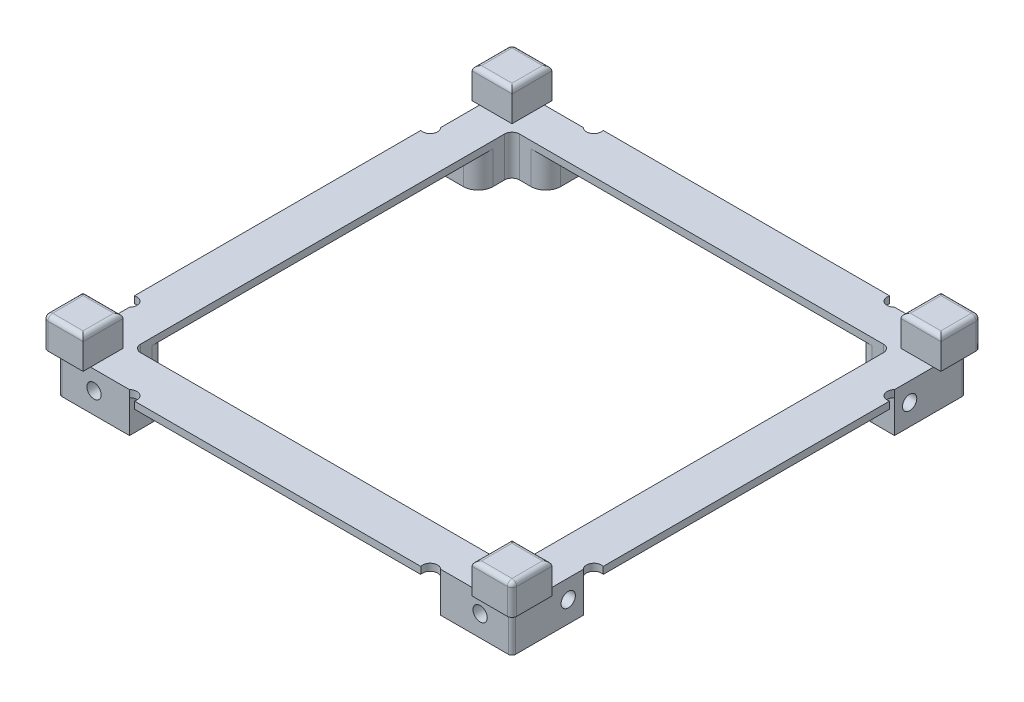
SolidWorks part; units mm, degrees
material "6061-T6 (SS)"
ref_plane "Front Plane" through (0, 0, 0) normal (0, 0, 1) x (1, 0, 0)
ref_plane "Top Plane" through (0, 0, 0) normal (0, 1, 0) x (1, 0, 0)
ref_plane "Right Plane" through (0, 0, 0) normal (1, 0, 0) x (0, 0, -1)
sketch "Sketch1" plane through (0, 0, 0) normal (0, 1, 0) x (1, 0, 0)
  line L1 (0, 0) -> (100, 0)
  line L2 (0, 0) -> (0, 100)
  line L3 (0, 100) -> (100, 100)
  line L4 (100, 0) -> (100, 100)
  dimension "D1" = 100
  dimension "D2" = 100
extrude "Boss-Extrude1" add sketch "Sketch1" along normal blind 8.5
sketch "Sketch2" plane through (0, 8.5, 0) normal (0, 1, 0) x (1, 0, 0)
  line L0 (0, 100) -> (19.05, 100)
  line L1 (100, 100) -> (0, 100) construction
  line L2 (0, 100) -> (0, 80.95)
  line L3 (0, 100) -> (0, 0) construction
  line L4 (1.5875, 98.4125) -> (1.5875, 83.1951)
  line L5 (1.5875, 98.4125) -> (16.8049, 98.4125)
  line L8 (1.5875, 80.95) -> (-2.2881, 84.8256) construction
  line L9 (19.05, 98.4125) -> (15.2408, 102.2217) construction
  line L10 (0, 80.95) -> (0, 80.5547)
  line L11 (1.5875, 98.4125) -> (1.5875, 80.95) construction
  line L12 (19.05, 100) -> (19.4453, 100)
  line L13 (1.5875, 98.4125) -> (19.05, 98.4125) construction
  line L14 (50, 100) -> (50, 0) construction
  line L15 (0, 0) -> (100, 0) construction
  line L16 (50, 0) -> (100, 50) construction
  line L17 (100, 0) -> (100, 100) construction
  line L18 (100, 50) -> (0, 50) construction
  line L19 (80.95, 98.4125) -> (84.7592, 102.2217) construction
  line L20 (98.4125, 80.95) -> (102.2881, 84.8256) construction
  line L21 (80.95, 100) -> (80.5547, 100)
  line L22 (100, 80.95) -> (100, 80.5547)
  line L23 (98.4125, 98.4125) -> (83.1951, 98.4125)
  line L24 (98.4125, 98.4125) -> (98.4125, 83.1951)
  line L25 (100, 100) -> (100, 80.95)
  line L26 (100, 100) -> (80.95, 100)
  line L27 (98.4125, 19.05) -> (102.2881, 15.1744) construction
  line L28 (80.95, 1.5875) -> (84.7592, -2.2217) construction
  line L29 (100, 0) -> (80.95, 0)
  line L30 (100, 0) -> (100, 19.05)
  line L31 (98.4125, 1.5875) -> (98.4125, 16.8049)
  line L32 (98.4125, 1.5875) -> (83.1951, 1.5875)
  line L33 (100, 19.05) -> (100, 19.4453)
  line L34 (80.95, 0) -> (80.5547, 0)
  line L35 (19.05, 1.5875) -> (15.2408, -2.2217) construction
  line L36 (1.5875, 19.05) -> (-2.2881, 15.1744) construction
  line L37 (19.05, 0) -> (19.4453, 0)
  line L38 (0, 19.05) -> (0, 19.4453)
  line L39 (1.5875, 1.5875) -> (16.8049, 1.5875)
  line L40 (1.5875, 1.5875) -> (1.5875, 16.8049)
  line L41 (0, 0) -> (0, 19.05)
  line L42 (0, 0) -> (19.05, 0)
  arc A1 (0, 83.5904) -> (-0.6576, 83.1951) centre (0.465, 82.0725) ccw
  arc A2 (16.8049, 98.4125) -> (19.4453, 100) centre (17.9275, 99.535) ccw
  arc A3 (0, 80.5547) -> (1.5875, 83.1951) centre (0.465, 82.0725) ccw
  arc A4 (100, 80.5547) -> (98.4125, 83.1951) centre (99.535, 82.0725) cw
  arc A5 (83.1951, 98.4125) -> (80.5547, 100) centre (82.0725, 99.535) cw
  arc A6 (100, 83.5904) -> (100.6576, 83.1951) centre (99.535, 82.0725) cw
  arc A7 (100, 16.4096) -> (100.6576, 16.8049) centre (99.535, 17.9275) ccw
  arc A8 (83.1951, 1.5875) -> (80.5547, 0) centre (82.0725, 0.465) ccw
  arc A9 (100, 19.4453) -> (98.4125, 16.8049) centre (99.535, 17.9275) ccw
  arc A10 (0, 19.4453) -> (1.5875, 16.8049) centre (0.465, 17.9275) cw
  arc A11 (16.8049, 1.5875) -> (19.4453, 0) centre (17.9275, 0.465) cw
  arc A12 (0, 16.4096) -> (-0.6576, 16.8049) centre (0.465, 17.9275) cw
  dimension "D4" = 45
  dimension "D5" = 1.5875
  dimension "D7" = 1.5875
  dimension "D1" = 19.05
  dimension "D2" = 19.05
  dimension "D6" = 45
  dimension "D3" = 1.5875
extrude "Cut-Extrude1" cut sketch "Sketch2" against normal through all
sketch "Sketch3" plane through (0, 8.5, 0) normal (0, 1, 0) x (1, 0, 0)
  line L0 (0, 50) -> (100, 50) construction
  line L5 (0, 0) -> (8.5, 0)
  line L6 (0, 0) -> (0, 8.5)
  line L7 (0, 8.5) -> (8.5, 8.5)
  line L8 (8.5, 0) -> (8.5, 8.5)
  line L9 (0, 80.5547) -> (0, 19.4453) construction
  line L10 (100, 19.4453) -> (100, 80.5547) construction
  line L11 (100, 50) -> (50, 100) construction
  line L12 (80.5547, 100) -> (19.4453, 100) construction
  line L13 (50, 100) -> (50, 0) construction
  line L14 (19.4453, 0) -> (80.5547, 0) construction
  line L15 (100, 8.5) -> (91.5, 8.5)
  line L16 (91.5, 0) -> (91.5, 8.5)
  line L17 (100, 0) -> (91.5, 0)
  line L18 (100, 0) -> (100, 8.5)
  line L19 (100, 100) -> (100, 91.5)
  line L20 (100, 100) -> (91.5, 100)
  line L21 (91.5, 100) -> (91.5, 91.5)
  line L22 (100, 91.5) -> (91.5, 91.5)
  line L23 (0, 91.5) -> (8.5, 91.5)
  line L24 (8.5, 100) -> (8.5, 91.5)
  line L25 (0, 100) -> (8.5, 100)
  line L26 (0, 100) -> (0, 91.5)
  dimension "D1" = 8.5
  dimension "D2" = 8.5
extrude "Boss-Extrude2" add sketch "Sketch3" along normal blind 6.5
sketch "Sketch10" plane through (0, 0, 0) normal (0, -1, 0) x (1, 0, 0)
  line L0 (100, -50) -> (0, -50) construction
  line L1 (100, -19.4453) -> (100, -80.5547) construction
  line L3 (0, -80.5547) -> (0, -19.4453) construction
  line L5 (50, 0) -> (50, -100) construction
  line L7 (19.4453, 0) -> (80.5547, 0) construction
  line L9 (80.5547, -100) -> (19.4453, -100) construction
  line L14 (90.005, -50) -> (90.005, -92.8625) construction
  line L15 (95.085, -2.0575) -> (4.915, -2.0575) construction
  line L16 (95.085, -2.0575) -> (95.085, -97.9425) construction
  line L17 (95.085, -97.9425) -> (4.915, -97.9425) construction
  line L18 (4.915, -2.0575) -> (4.915, -97.9425) construction
  line L19 (95.085, -2.0575) -> (4.915, -97.9425) construction
  line L20 (95.085, -97.9425) -> (4.915, -2.0575) construction
  line L21 (86.195, -50) -> (86.195, -7.1375) construction
  line L22 (12.535, -50) -> (12.535, -7.1375) construction
  line L23 (9.995, -50) -> (9.995, -92.8625) construction
  point P21 (50, -50)
  point P35 (12.535, -7.1375)
  point P36 (9.995, -92.8625)
  point P37 (90.005, -92.8625)
  point P38 (86.195, -7.1375)
  dimension "D1" = 95.885
  dimension "D2" = 90.17
  dimension "D3" = 5.08
  dimension "D4" = 8.89
  dimension "D5" = 5.08
  dimension "D6" = 5.08
  dimension "D7" = 7.62
  dimension "D8" = 5.08
  dimension "D9" = 5.08
  dimension "D10" = 5.08
hole_wizard "Tap Drill for #4 Helicoil5" positions "Sketch11" profile "Sketch12" hole size "#4-40" standard "ANSI Inch"
sketch "Sketch11" plane through (0, 0, 0) normal (0, -1, 0) x (-1, 0, 0)
  point P14 (-86.195, 7.1375)
  point P17 (-90.005, 92.8625)
  point P20 (-12.535, 7.1375)
  point P23 (-9.995, 92.8625)
sketch "Sketch12" plane through (86.195, 0, -7.1375) normal (1, 0, 0) x (0, 0, -1)
  line L0 (0, 0) -> (0, 6.6057)
  line L1 (0, 6.6057) -> (1.524, 5.69)
  line L2 (1.524, 5.69) -> (1.524, 0)
  line L5 (1.524, 0) -> (0, 0)
  line L10 (0, 6.6057) -> (-1.524, 5.69) construction
  line L11 (0, -6.35) -> (0, 107.95) construction
  dimension "Hole Dia." = 3.048
  dimension "Hole Depth" = 5.69
  dimension "Drill Angle" = 118
sketch "Sketch13" plane through (0, 15, 0) normal (0, 1, 0) x (1, 0, 0)
  line L0 (0, 50) -> (100, 50) construction
  line L1 (0, 0) -> (100, 0) construction
  line L2 (0, 0) -> (0, 100) construction
  line L3 (0, 100) -> (100, 100) construction
  line L4 (100, 0) -> (100, 100) construction
  line L5 (100, 50) -> (50, 100) construction
  line L6 (50, 100) -> (50, 0) construction
  line L7 (100, 0) -> (100, 4.25) construction
  line L8 (100, 4.25) -> (95.75, 4.25) construction
  point P11 (95.75, 95.75)
  point P13 (95.75, 4.25)
  point P14 (4.25, 95.75)
  point P15 (4.25, 4.25)
  dimension "D1" = 4.25
  dimension "D2" = 4.25
sketch "Sketch16" plane through (1.5875, 0, 0) normal (-1, 0, 0) x (0, 0, 1)
  line L0 (-98.4125, 4.5) -> (-83.1951, 4.5) construction
  line L1 (-98.4125, 0) -> (-98.4125, 8.5) construction
  line L4 (-91.5, 8.5) -> (-83.1951, 8.5) construction
  point P6 (-86.4125, 4.5)
  dimension "D1" = 12
  dimension "D2" = 4
hole_wizard "Tap Drill for #4 Helicoil5" positions "Sketch17" profile "Sketch18" hole size "#4-40" standard "ANSI Inch"
sketch "Sketch17" plane through (1.5875, 0, 0) normal (-1, 0, 0) x (0, 0, 1)
  point P0 (-86.4125, 4.5)
sketch "Sketch18" plane through (1.5875, 4.5, -86.4125) normal (0, 1, 0) x (0, 0, 1)
  line L0 (0, 0) -> (0, 6.6057)
  line L1 (0, 6.6057) -> (1.524, 5.69)
  line L2 (1.524, 5.69) -> (1.524, 0)
  line L5 (1.524, 0) -> (0, 0)
  line L10 (0, 6.6057) -> (-1.524, 5.69) construction
  line L11 (0, -6.35) -> (0, 107.95) construction
  dimension "Hole Dia." = 3.048
  dimension "Hole Depth" = 5.69
  dimension "Drill Angle" = 118
ref_plane "Plane6" through (50, 0, 0) normal (-1, 0, 0) x (0, 0, 1)
ref_plane "Plane7" through (0, 0, -50) normal (0, 0, -1) x (-1, 0, 0)
mirror "Mirror1" about plane through (0, 0, -50) normal (0, 0, -1) of "Tap Drill for #4 Helicoil5"
mirror "Mirror2" about plane through (50, 0, 0) normal (-1, 0, 0) of "Mirror1", "Tap Drill for #4 Helicoil5"
sketch "Sketch19" plane through (0, 0, -98.4125) normal (0, 0, -1) x (-1, 0, 0)
  line L0 (-1.5875, 4.5) -> (-16.8049, 4.5) construction
  line L2 (-1.5875, 0) -> (-1.5875, 8.5) construction
  line L3 (-8.5, 8.5) -> (-16.8049, 8.5) construction
  point P5 (-13.5875, 4.5)
  dimension "D1" = 12
  dimension "D2" = 4
hole_wizard "Tap Drill for #4 Helicoil5" positions "Sketch20" profile "Sketch21" hole size "#4-40" standard "ANSI Inch"
sketch "Sketch20" plane through (0, 0, -98.4125) normal (0, 0, -1) x (-1, 0, 0)
  point P0 (-13.5875, 4.5)
sketch "Sketch21" plane through (13.5875, 4.5, -98.4125) normal (1, 0, 0) x (0, 1, 0)
  line L0 (0, 0) -> (0, 6.6057)
  line L1 (0, 6.6057) -> (1.524, 5.69)
  line L2 (1.524, 5.69) -> (1.524, 0)
  line L5 (1.524, 0) -> (0, 0)
  line L10 (0, 6.6057) -> (-1.524, 5.69) construction
  line L11 (0, -6.35) -> (0, 107.95) construction
  dimension "Hole Dia." = 3.048
  dimension "Hole Depth" = 5.69
  dimension "Drill Angle" = 118
mirror "Mirror3" about plane through (50, 0, 0) normal (-1, 0, 0) of "Tap Drill for #4 Helicoil5"
sketch "Sketch33" plane through (0, 0, -1.5875) normal (0, 0, 1) x (1, 0, 0)
  line L2 (91.5, 8.5) -> (83.1951, 8.5) construction
  line L3 (98.4125, 0) -> (98.4125, 8.5) construction
  point P5 (91.6125, 4.5)
  dimension "D3" = 4
  dimension "D4" = 6.8
hole_wizard "Tap Drill for #4 Helicoil5" positions "Sketch34" profile "Sketch35" hole size "#4-40" standard "ANSI Inch"
sketch "Sketch34" plane through (0, 0, -1.5875) normal (0, 0, 1) x (1, 0, 0)
  point P6 (91.6125, 4.5)
sketch "Sketch35" plane through (91.6125, 4.5, -1.5875) normal (1, 0, 0) x (0, -1, 0)
  line L0 (0, 0) -> (0, 6.6057)
  line L1 (0, 6.6057) -> (1.524, 5.69)
  line L2 (1.524, 5.69) -> (1.524, 0)
  line L5 (1.524, 0) -> (0, 0)
  line L10 (0, 6.6057) -> (-1.524, 5.69) construction
  line L11 (0, -6.35) -> (0, 107.95) construction
  dimension "Hole Dia." = 3.048
  dimension "Hole Depth" = 5.69
  dimension "Drill Angle" = 118
sketch "Sketch22" plane through (0, 0, 0) normal (0, -1, 0) x (1, 0, 0)
  line L0 (50, 0) -> (50, -100) construction
  line L5 (83.1951, -9.5875) -> (88.825, -9.5875)
  line L6 (90.4125, -11.175) -> (90.4125, -16.8049)
  line L7 (50, -100) -> (0, -50) construction
  line L8 (0, -50) -> (100, -50) construction
  line L9 (1.5875, -16.8049) -> (9.5875, -16.8049)
  line L10 (16.8049, -1.5875) -> (16.8049, -9.5875)
  line L11 (9.5875, -11.175) -> (9.5875, -16.8049)
  line L12 (16.8049, -9.5875) -> (11.175, -9.5875)
  line L13 (83.1951, -1.5875) -> (83.1951, -9.5875)
  line L14 (98.4125, -16.8049) -> (90.4125, -16.8049)
  line L15 (98.4125, -83.1951) -> (90.4125, -83.1951)
  line L16 (83.1951, -98.4125) -> (83.1951, -90.4125)
  line L17 (16.8049, -90.4125) -> (11.175, -90.4125)
  line L18 (9.5875, -88.825) -> (9.5875, -83.1951)
  line L19 (16.8049, -98.4125) -> (16.8049, -90.4125)
  line L20 (1.5875, -83.1951) -> (9.5875, -83.1951)
  line L21 (90.4125, -88.825) -> (90.4125, -83.1951)
  line L22 (83.1951, -90.4125) -> (88.825, -90.4125)
  line L23 (1.5875, -83.1951) -> (0, -83.1951)
  line L24 (0, -83.1951) -> (0, -16.8049)
  line L25 (0, -16.8049) -> (1.5875, -16.8049)
  line L26 (16.8049, -1.5875) -> (16.8049, 0)
  line L27 (16.8049, 0) -> (83.1951, 0)
  line L28 (0, 0) -> (100, 0) construction
  line L29 (83.1951, 0) -> (83.1951, -1.5875)
  line L30 (98.4125, -83.1951) -> (100, -83.1951)
  line L31 (100, -16.8049) -> (98.4125, -16.8049)
  line L32 (100, -83.1951) -> (100, -16.8049)
  line L33 (16.8049, -98.4125) -> (16.8049, -100)
  line L34 (83.1951, -100) -> (83.1951, -98.4125)
  line L35 (16.8049, -100) -> (83.1951, -100)
  line L36 (80.5547, -100) -> (19.4453, -100) construction
  arc A4 (9.5875, -11.175) -> (11.175, -9.5875) centre (11.175, -11.175) cw
  arc A5 (90.4125, -11.175) -> (88.825, -9.5875) centre (88.825, -11.175) ccw
  arc A6 (90.4125, -88.825) -> (88.825, -90.4125) centre (88.825, -88.825) cw
  arc A7 (9.5875, -88.825) -> (11.175, -90.4125) centre (11.175, -88.825) ccw
  point P0 (50, -50)
  point P19 (90.4125, -9.5875)
  point P30 (9.5875, -9.5875)
  point P44 (9.5875, -90.4125)
  point P45 (90.4125, -90.4125)
  dimension "D4" = 1.5875
  dimension "D2" = 8
  dimension "D3" = 8
extrude "Cut-Extrude2" cut sketch "Sketch22" against normal blind 7
sketch "Sketch23" plane through (0, 7, 0) normal (0, -1, 0) x (1, 0, 0)
  line L0 (0, -50) -> (100, -50) construction
  line L1 (0, -19.4453) -> (0, -80.5547) construction
  line L2 (100, -80.5547) -> (100, -19.4453) construction
  line L4 (11.175, -90.4125) -> (88.825, -90.4125)
  line L5 (9.5875, -88.825) -> (9.5875, -11.175)
  line L6 (11.175, -9.5875) -> (88.825, -9.5875)
  line L7 (90.4125, -88.825) -> (90.4125, -11.175)
  line L8 (9.5875, -90.4125) -> (90.4125, -9.5875) construction
  line L9 (9.5875, -9.5875) -> (90.4125, -90.4125) construction
  arc A0 (90.4125, -88.825) -> (88.825, -90.4125) centre (88.825, -88.825) cw
  arc A1 (88.825, -9.5875) -> (90.4125, -11.175) centre (88.825, -11.175) cw
  arc A2 (11.175, -9.5875) -> (9.5875, -11.175) centre (11.175, -11.175) ccw
  arc A3 (9.5875, -88.825) -> (11.175, -90.4125) centre (11.175, -88.825) ccw
  arc A4 (9.5875, -88.825) -> (11.175, -90.4125) centre (11.175, -88.825) ccw construction
  point P6 (50, -50)
  dimension "D3" = 1.5875
extrude "Cut-Extrude3" cut sketch "Sketch23" against normal through all
fillet "Fillet1" radius 1 20 edges at (95.75, 15, 0) (100, 15, -4.25) (91.5, 15, -4.25) (95.75, 15, -8.5) (4.25, 15, 0) (8.5, 15, -4.25) (0, 15, -4.25) (4.25, 15, -8.5) (4.25, 15, -91.5) (8.5, 15, -95.75) (0, 15, -95.75) (4.25, 15, -100) (100, 15, -95.75) (95.75, 15, -91.5) (91.5, 15, -95.75) (95.75, 15, -100) (100, 11.75, -100) (0, 11.75, -100) (0, 11.75, 0) (100, 11.75, 0)
fillet "Fillet2" radius 3.175 8 edges at (9.5875, 3.5, -16.8049) (16.8049, 3.5, -9.5875) (9.5875, 3.5, -83.1951) (16.8049, 3.5, -90.4125) (83.1951, 3.5, -90.4125) (90.4125, 3.5, -83.1951) (83.1951, 3.5, -9.5875) (90.4125, 3.5, -16.8049)
fillet "Fillet3" radius 0.79 4 edges at (1.5875, 4.25, -1.5875) (98.4125, 4.25, -1.5875) (98.4125, 4.25, -98.4125) (1.5875, 4.25, -98.4125)
sketch "Sketch36" plane through (0, 0, -1.5875) normal (0, 0, 1) x (1, 0, 0)
  line L2 (8.5, 8.5) -> (16.8049, 8.5) construction
  line L3 (1.5875, 0) -> (1.5875, 8.5) construction
  point P5 (9.2475, 4.5)
  dimension "D3" = 4
  dimension "D4" = 7.66
hole_wizard "Tap Drill for #4 Helicoil5" positions "Sketch37" profile "Sketch38" hole size "#4-40" standard "ANSI Inch"
sketch "Sketch37" plane through (0, 0, -1.5875) normal (0, 0, 1) x (1, 0, 0)
  point P4 (9.2475, 4.5)
sketch "Sketch38" plane through (9.2475, 4.5, -1.5875) normal (1, 0, 0) x (0, -1, 0)
  line L0 (0, 0) -> (0, 6.6057)
  line L1 (0, 6.6057) -> (1.524, 5.69)
  line L2 (1.524, 5.69) -> (1.524, 0)
  line L5 (1.524, 0) -> (0, 0)
  line L10 (0, 6.6057) -> (-1.524, 5.69) construction
  line L11 (0, -6.35) -> (0, 107.95) construction
  dimension "Hole Dia." = 3.048
  dimension "Hole Depth" = 5.69
  dimension "Drill Angle" = 118
sketch "Sketch24" [suppressed] plane through (0, 15, 0) normal (0, 1, 0) x (1, 0, 0)
  line L0 (4.25, 99) -> (4.25, 92.5) construction
  line L3 (7.5, 99) -> (1, 99) construction
  line L6 (1, 92.5) -> (7.5, 92.5) construction
  line L7 (95.75, 7.5) -> (95.75, 1) construction
  line L8 (99, 7.5) -> (92.5, 7.5) construction
  line L9 (92.5, 1) -> (99, 1) construction
  point P14 (95.75, 4.25)
  point P15 (4.25, 95.75)
hole_wizard "Tap Drill for #8-32 Tap1" positions "Sketch25" profile "Sketch26" hole size "#8-32" standard "ANSI Inch"
sketch "Sketch25" plane through (0, 15, 0) normal (0, 1, 0) x (1, 0, 0)
  point P7 (4.25, 95.75)
  point P10 (95.75, 4.25)
sketch "Sketch26" plane through (4.25, 15, -95.75) normal (1, 0, 0) x (0, 0, 1)
  line L0 (0, 0) -> (0, 12.1376)
  line L1 (0, 12.1376) -> (1.7272, 11.0998)
  line L2 (1.7272, 11.0998) -> (1.7272, 0)
  line L5 (1.7272, 0) -> (0, 0)
  line L10 (0, 12.1376) -> (-1.7272, 11.0998) construction
  line L11 (0, -6.35) -> (0, 107.95) construction
  dimension "Hole Dia." = 3.4544
  dimension "Hole Depth" = 11.0998
  dimension "Drill Angle" = 118
sketch "Sketch27" [suppressed] plane through (0, 15, 0) normal (0, 1, 0) x (1, 0, 0)
  line L6 (95.75, 99) -> (95.75, 92.5) construction
  line L7 (99, 99) -> (92.5, 99) construction
  line L8 (92.5, 92.5) -> (99, 92.5) construction
  line L9 (4.25, 7.5) -> (4.25, 1) construction
  line L10 (7.5, 7.5) -> (1, 7.5) construction
  line L11 (1, 1) -> (7.5, 1) construction
  circle A2 centre (95.75, 95.75) radius 2.8575
  circle A3 centre (4.25, 4.25) radius 2.8575
  dimension "D1" = 5.715
  dimension "D3" = 5.715
extrude "Cut-Extrude4" [suppressed] cut sketch "Sketch27" against normal blind 2.032
sketch "Sketch28" [suppressed] plane through (0, 12.968, 0) normal (0, 1, 0) x (1, 0, 0)
  circle A2 centre (95.75, 95.75) radius 2.286
  circle A3 centre (4.25, 4.25) radius 2.286
  dimension "D1" = 4.572
  dimension "D2" = 4.572
extrude "Cut-Extrude5" [suppressed] cut sketch "Sketch28" against normal blind 4.318
sketch "Sketch29" [suppressed] plane through (0, 8.65, 0) normal (0, 1, 0) x (1, 0, 0)
  point P3 (95.75, 95.75)
  point P5 (4.25, 4.25)
hole_wizard "#4 Clearance Hole1" positions "Sketch30" profile "Sketch31" hole size "#4" standard "ANSI Inch"
sketch "Sketch30" plane through (0, 8.65, 0) normal (0, 1, 0) x (1, 0, 0)
  point P7 (4.25, 4.25)
  point P16 (95.75, 95.75)
sketch "Sketch31" plane through (4.25, 8.65, -4.25) normal (1, 0, 0) x (0, 0, 1)
  line L0 (0, 0) -> (0, 8.65)
  line L1 (0, 8.65) -> (1.7272, 8.65)
  line L2 (1.7272, 8.65) -> (1.7272, 0)
  line L5 (1.7272, 0) -> (0, 0)
  line L11 (0, -6.35) -> (0, 107.95) construction
  dimension "Thru Hole Dia." = 3.4544
  dimension "Thru Hole Depth" = 8.65
sketch "Sketch40" [suppressed] plane through (0, 8.5, 0) normal (0, 1, 0) x (1, 0, 0)
  text T0 "<r270>1</r>"
  text T1 "<r270>2</r>"
  text T2 "<r270>3</r>"
  text T3 "<r270>4</r>"
sketch "Sketch42" plane through (0, 8.5, 0) normal (0, 1, 0) x (1, 0, 0)
  text T0 "<r270>1</r>"
  text T1 "<r270>2</r>"
  text T2 "<r270>3</r>"
  text T3 "<r270>4</r>"
